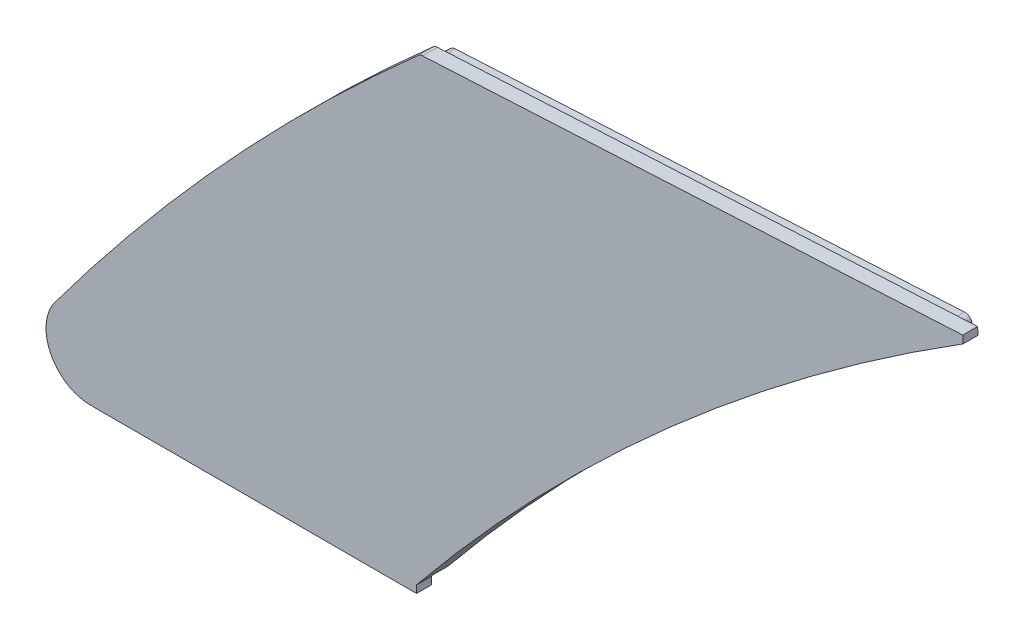
SolidWorks part; units mm, degrees
ref_plane "Front Plane" through (0, 0, 0) normal (0, 0, 1) x (1, 0, 0)
ref_plane "Top Plane" through (0, 0, 0) normal (0, 1, 0) x (1, 0, 0)
ref_plane "Right Plane" through (0, 0, 0) normal (1, 0, 0) x (0, 0, -1)
sketch "Sketch2" plane through (0, 0, 4) normal (0, 0, 1) x (1, 0, 0)
  line L0 (-44.3055, -62) -> (-0.9492, -62) construction
  line L1 (69.2315, 2.6269) -> (0.75, -0.9621) construction
  line L2 (-44.3055, -62) -> (-0.9492, -62)
  line L3 (69.2315, 2.6269) -> (0.75, -0.9621)
  line L4 (69.2838, 1.6283) -> (0.8023, -1.9607)
  line L5 (-44.3055, -61) -> (-0.9492, -61)
  arc A0 (69.8249, 0.7873) -> (69.2315, 2.6269) centre (69.2838, 1.6283) ccw construction
  arc A1 (73.0381, 2.8264) -> (-0.4751, -62) centre (232.7073, -252.3339) ccw construction
  arc A2 (-48.317, -54.0155) -> (-44.3055, -62) centre (-44.3055, -57) ccw construction
  arc A3 (0.75, -0.9621) -> (0.1388, -1.2125) centre (0.8023, -1.9607) ccw construction
  arc A4 (0.1388, -1.2125) -> (-48.317, -54.0155) centre (231.6898, -262.3354) ccw construction
  arc A5 (69.8249, 0.7873) -> (69.2315, 2.6269) centre (69.2838, 1.6283) ccw
  arc A6 (69.8249, 0.7873) -> (-0.1755, -61.6336) centre (232.7073, -252.3339) ccw
  arc A7 (-48.317, -54.0155) -> (-44.3055, -62) centre (-44.3055, -57) ccw
  arc A8 (0.75, -0.9621) -> (0.1388, -1.2125) centre (0.8023, -1.9607) ccw
  arc A9 (0.1388, -1.2125) -> (-48.317, -54.0155) centre (231.6898, -262.3354) ccw
  arc A10 (-0.9492, -62) -> (-0.1755, -61.6336) centre (-0.9492, -61) ccw construction
  arc A11 (-0.9492, -62) -> (-0.1755, -61.6336) centre (-0.9492, -61) ccw
  arc A12 (69.2838, 1.6283) -> (69.2838, 1.6283) centre (69.2838, 1.6283) ccw
  arc A13 (0.8023, -1.9607) -> (0.8023, -1.9607) centre (0.8023, -1.9607) ccw
  arc A14 (0.8023, -1.9607) -> (-47.5147, -54.6124) centre (231.6898, -262.3354) ccw
  arc A15 (-47.5147, -54.6124) -> (-44.3055, -61) centre (-44.3055, -57) ccw
  arc A16 (-0.9492, -61) -> (-0.9492, -61) centre (-0.9492, -61) ccw
  arc A17 (69.2838, 1.6283) -> (-0.9492, -61) centre (232.7073, -252.3339) ccw
  dimension "D1" = 1
extrude "Boss-Extrude1" add sketch "Sketch2" against normal blind 2
sketch "Sketch3" plane through (0, 0, 4) normal (0, 0, 1) x (1, 0, 0)
  line L6 (0.75, -0.9621) -> (69.2315, 2.6269)
  line L7 (73.0381, 2.8264) -> (72.9858, 3.825)
  line L8 (72.9858, 3.825) -> (0.3485, 0.0183)
  line L9 (-44.3055, -63) -> (-0.4751, -63)
  line L10 (-0.4751, -63) -> (-0.4751, -62)
  line L11 (-0.9492, -62) -> (-44.3055, -62)
  line L13 (73.0381, 2.8264) -> (72.9858, 3.825)
  line L14 (72.9858, 3.825) -> (0.3485, 0.0183)
  line L15 (-44.3055, -63) -> (-0.4751, -63)
  line L16 (-0.4751, -63) -> (-0.4751, -62)
  arc A0 (73.0381, 2.8264) -> (-0.4751, -62) centre (232.7073, -252.3339) ccw construction
  arc A1 (73.0381, 2.8264) -> (-0.4751, -62) centre (232.7073, -252.3339) ccw
  arc A10 (69.8249, 0.7873) -> (69.2315, 2.6269) centre (69.2838, 1.6283) ccw
  arc A11 (73.0381, 2.8264) -> (69.8249, 0.7873) centre (232.7073, -252.3339) ccw
  arc A12 (0.3485, 0.0183) -> (-0.2619, -0.2315) centre (0.4009, -0.9804) ccw
  arc A13 (-0.2619, -0.2315) -> (-49.1194, -53.4186) centre (231.6898, -262.3354) ccw
  arc A14 (-49.1194, -53.4186) -> (-44.3055, -63) centre (-44.3055, -57) ccw
  arc A15 (-0.1755, -61.6336) -> (-0.4751, -62) centre (232.7073, -252.3339) ccw
  arc A16 (-0.9492, -62) -> (-0.1755, -61.6336) centre (-0.9492, -61) ccw
  arc A17 (-48.317, -54.0155) -> (-44.3055, -62) centre (-44.3055, -57) ccw
  arc A18 (0.1388, -1.2125) -> (-48.317, -54.0155) centre (231.6898, -262.3354) ccw
  arc A19 (0.75, -0.9621) -> (0.1388, -1.2125) centre (0.8023, -1.9607) ccw
  arc A22 (0.3485, 0.0183) -> (-0.2619, -0.2315) centre (0.4009, -0.9804) ccw
  arc A23 (-0.2619, -0.2315) -> (-49.1194, -53.4186) centre (231.6898, -262.3354) ccw
  arc A24 (-49.1194, -53.4186) -> (-44.3055, -63) centre (-44.3055, -57) ccw
  dimension "D1" = 0
extrude "Boss-Extrude2" add sketch "Sketch3" along normal blind 2
